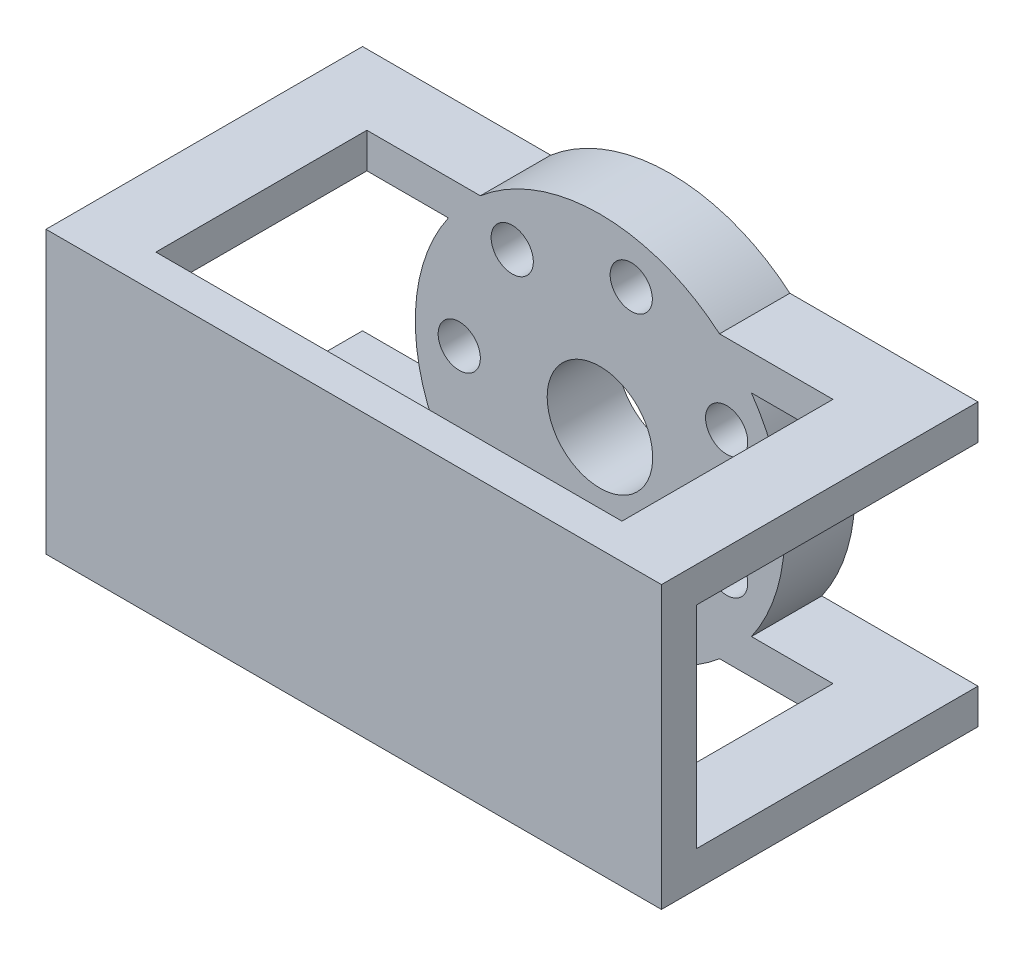
SolidWorks part; units mm, degrees
ref_plane "Front Plane" through (0, 0, 0) normal (0, 0, 1) x (1, 0, 0)
ref_plane "Top Plane" through (0, 0, 0) normal (0, 1, 0) x (1, 0, 0)
ref_plane "Right Plane" through (0, 0, 0) normal (1, 0, 0) x (0, 0, -1)
sketch "Sketch1" plane through (0, 0, 0) normal (0, 1, 0) x (1, 0, 0)
  line L1 (-87.5, 45) -> (87.5, 45)
  line L2 (-87.5, 45) -> (-87.5, -45)
  line L3 (-87.5, -45) -> (87.5, -45)
  line L4 (87.5, 45) -> (87.5, -45)
  line L5 (-87.5, 45) -> (87.5, -45) construction
  line L6 (-87.5, -45) -> (87.5, 45) construction
  point P0 (0, 0)
  dimension "D1" = 175
  dimension "D2" = 90
extrude "Boss-Extrude1" add sketch "Sketch1" along normal blind 80
sketch "Sketch4" plane through (-87.5, 0, 0) normal (-1, 0, 0) x (0, 0, 1)
  line L0 (0, 0) -> (0, 80) construction
  line L1 (-45, 0) -> (45, 0) construction
  line L2 (-45, 80) -> (45, 80) construction
  line L4 (-35, 70) -> (35, 70)
  line L6 (-35, 10) -> (35, 10)
  line L7 (35, 70) -> (35, 10)
  line L8 (-35, 70) -> (35, 10) construction
  line L9 (-35, 10) -> (35, 70) construction
  line L10 (-35, 70) -> (-45, 70)
  line L11 (-45, 80) -> (-45, 0) construction
  line L12 (-35, 10) -> (-45, 10)
  point P6 (0, 40)
  line M10 (-45, 80) -> (-45, 0)
  dimension "D1" = 60
  dimension "D2" = 70
extrude "Cut-Extrude4" cut sketch "Sketch4" against normal blind 175 and the other way through all contours L12 L6 L7 L4 L10 M10
sketch "Sketch5" plane through (0, 80, 0) normal (0, 1, 0) x (1, 0, 0)
  line L1 (-66.26, 25) -> (66.26, 25)
  line L5 (-66.26, -35) -> (66.26, -35)
  line L6 (-66.26, 25) -> (-66.26, -35)
  line L10 (66.26, 25) -> (66.26, -35)
  point P0 (0, 0)
  dimension "D3" = 132.5199
extrude "Cut-Extrude5" cut sketch "Sketch5" against normal blind 175
sketch "Sketch6" plane through (0, 0, -45) normal (0, 0, -1) x (-1, 0, 0)
  line L0 (0, 0) -> (0, 80) construction
  line L1 (-87.5, 80) -> (87.5, 80) construction
  line L2 (-128.1399, 40) -> (128.1399, 40) construction
  line L3 (-87.5, 0) -> (87.5, 0) construction
  line L4 (87.5, 10) -> (-87.5, 10) construction
  line L5 (87.5, 70) -> (-87.5, 70) construction
  line L6 (-87.5, 0) -> (-34.0037, 0)
  line L7 (87.5, 10) -> (43.0842, 10)
  line L8 (-87.5, 80) -> (-34.0037, 80)
  line L9 (87.5, 70) -> (43.0842, 70)
  line L10 (-87.5, 80) -> (-87.5, 70) construction
  line L11 (87.5, 80) -> (87.5, 70) construction
  line L12 (87.5, 10) -> (87.5, 0) construction
  line L13 (-87.5, 10) -> (-87.5, 0) construction
  line L14 (87.5, 80) -> (87.5, 70)
  line L15 (87.5, 10) -> (87.5, 0)
  line L16 (-87.5, 10) -> (-87.5, 0)
  line L17 (-87.5, 80) -> (-87.5, 70)
  line L18 (34.0037, 80) -> (87.5, 80)
  line L19 (-43.0842, 70) -> (-87.5, 70)
  line L20 (-43.0842, 10) -> (-87.5, 10)
  line L21 (34.0037, 0) -> (87.5, 0)
  arc A0 (-43.0842, 70) -> (-43.0842, 10) centre (0, 40) ccw
  arc A1 (34.0037, 80) -> (-34.0037, 80) centre (0, 40) ccw
  arc A2 (43.0842, 10) -> (43.0842, 70) centre (0, 40) ccw
  arc A3 (-34.0037, 0) -> (34.0037, 0) centre (0, 40) ccw
  point P8 (0, 40)
  dimension "D1" = 105
extrude "Boss-Extrude2" add sketch "Sketch6" against normal blind 20
sketch "Sketch7" plane through (0, 0, -45) normal (0, 0, -1) x (-1, 0, 0)
  line L0 (0, -12.5) -> (0, 92.5) construction
  arc A0 (-34.0037, 0) -> (34.0037, 0) centre (0, 40) ccw construction
  arc A1 (34.0037, 80) -> (-34.0037, 80) centre (0, 40) ccw construction
  circle A2 centre (0, 40) radius 40 construction
  circle A3 centre (0, 40) radius 15
  circle A5 centre (40, 40) radius 6
  circle A6 centre (24.9396, 8.7267) radius 6
  circle A7 centre (-8.9008, 1.0029) radius 6
  circle A8 centre (-36.0388, 22.6447) radius 6
  circle A9 centre (-36.0388, 57.3553) radius 6
  circle A10 centre (-8.9008, 78.9971) radius 6
  circle A11 centre (24.9396, 71.2733) radius 6
  point P27 (0, 40)
  dimension "D1" = 30
  dimension "D2" = 12
  dimension "D3" = 7
extrude "Cut-Extrude8" cut sketch "Sketch7" against normal blind 20
